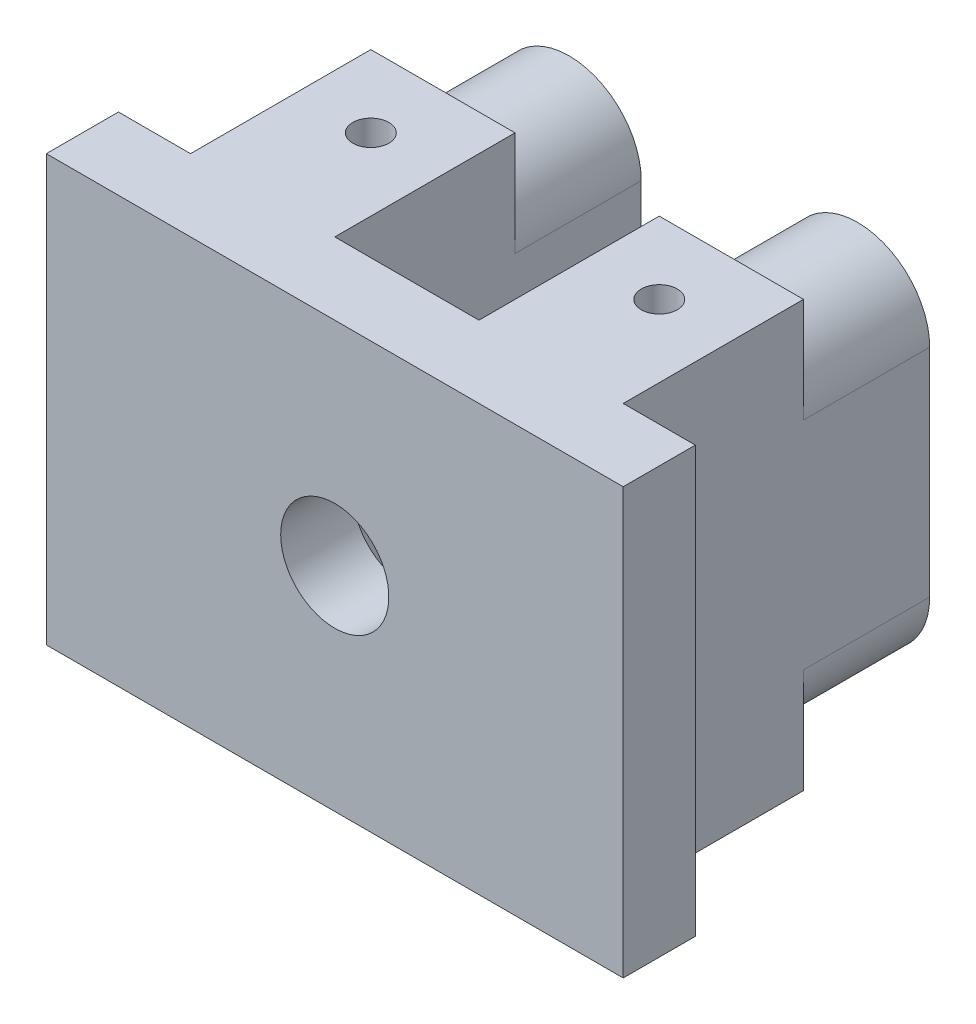
SolidWorks part; units mm, degrees
ref_plane "Front Plane" through (0, 0, 0) normal (0, 0, 1) x (1, 0, 0)
ref_plane "Top Plane" through (0, 0, 0) normal (0, 1, 0) x (1, 0, 0)
ref_plane "Right Plane" through (0, 0, 0) normal (1, 0, 0) x (0, 0, -1)
sketch "Sketch1" plane through (0, 0, 0) normal (0, 1, 0) x (1, 0, 0)
  line L0 (0, 0) -> (8, 0)
  line L1 (8, 0) -> (8, 2)
  line L2 (8, 2) -> (6, 2)
  line L3 (6, 2) -> (6, 7)
  line L4 (6, 7) -> (2, 7)
  line L5 (2, 7) -> (2, 2)
  line L6 (2, 2) -> (-2, 2)
  line L7 (-2, 2) -> (-2, 7)
  line L8 (-2, 7) -> (-6, 7)
  line L9 (-6, 7) -> (-6, 2)
  line L10 (-6, 2) -> (-8, 2)
  line L11 (-8, 2) -> (-8, 0)
  line L12 (-8, 0) -> (0, 0)
  line L13 (0, 2) -> (0, 0) construction
  point P15 (-4, 7)
  point P16 (4, 7)
  dimension "D1" = 16
  dimension "D2" = 2
  dimension "D3" = 8
  dimension "D4" = 4
  dimension "D5" = 7
extrude "Boss-Extrude1" add sketch "Sketch1" along normal blind 11.8
sketch "Sketch4" plane through (0, 0, 0) normal (0, 0, 1) x (1, 0, 0)
  line L0 (-4, 8.9) -> (-4, 2.9) construction
  line L1 (-2, 8.9) -> (-2, 2.9)
  line L2 (-6, 8.9) -> (-6, 2.9)
  line L3 (4, 8.9) -> (4, 2.9) construction
  line L4 (6, 8.9) -> (6, 2.9)
  line L5 (2, 8.9) -> (2, 2.9)
  line L6 (-4, 5.9) -> (4, 5.9) construction
  line L7 (-8, 11.8) -> (-8, 0) construction
  arc A0 (-2, 8.9) -> (-6, 8.9) centre (-4, 8.9) ccw
  arc A1 (-6, 2.9) -> (-2, 2.9) centre (-4, 2.9) ccw
  arc A2 (6, 8.9) -> (2, 8.9) centre (4, 8.9) ccw
  arc A3 (2, 2.9) -> (6, 2.9) centre (4, 2.9) ccw
  point P2 (-4, 5.9)
  point P7 (4, 5.9)
  point P16 (0, 5.9)
  point P19 (-8, 5.9)
  dimension "D1" = 2
  dimension "D2" = 8
  dimension "D3" = 6
extrude "Boss-Extrude2" add sketch "Sketch4" against normal blind 10.5
sketch "Sketch2" plane through (0, 11.8, 0) normal (0, 1, 0) x (1, 0, 0)
  line L0 (-4, 5) -> (-4, 7) construction
  line L2 (-2, 7) -> (-6, 7) construction
  line L3 (4, 5) -> (4, 7) construction
  line L4 (6, 7) -> (2, 7) construction
  line L5 (-8, 0) -> (8, 0) construction
  circle A0 centre (-4, 5) radius 0.5
  circle A1 centre (4, 5) radius 0.5
  dimension "D1" = 1
  dimension "D2" = 5
extrude "Cut-Extrude1" cut sketch "Sketch2" against normal through all both and the other way through all
sketch "Sketch5" plane through (0, 0, -10.5) normal (0, 0, -1) x (-1, 0, 0)
  circle A1 centre (4, 8.9) radius 1.1
  circle A2 centre (4, 2.9) radius 1.1
  circle A3 centre (-4, 2.9) radius 1.1
  circle A4 centre (-4, 8.9) radius 1.1
  dimension "D1" = 2.2
extrude "Cut-Extrude2" cut sketch "Sketch5" against normal blind 1
sketch "Sketch6" plane through (0, 0, -2) normal (0, 0, -1) x (-1, 0, 0)
  line L0 (-8, 11.8) -> (8, 0) construction
  circle A0 centre (0, 5.9) radius 1.5
  point P4 (0, 5.9)
  dimension "D1" = 3
extrude "Cut-Extrude3" cut sketch "Sketch6" against normal through all both and the other way through all
sketch "Sketch7" plane through (0, 0, -9.5) normal (0, 0, -1) x (-1, 0, 0)
  circle A0 centre (-4, 2.9) radius 0.5
  circle A1 centre (-4, 8.9) radius 0.5
  circle A2 centre (4, 8.9) radius 0.5
  circle A3 centre (4, 2.9) radius 0.5
  dimension "D1" = 1
extrude "Cut-Extrude4" [suppressed] cut sketch "Sketch7" against normal through all both and the other way through all
